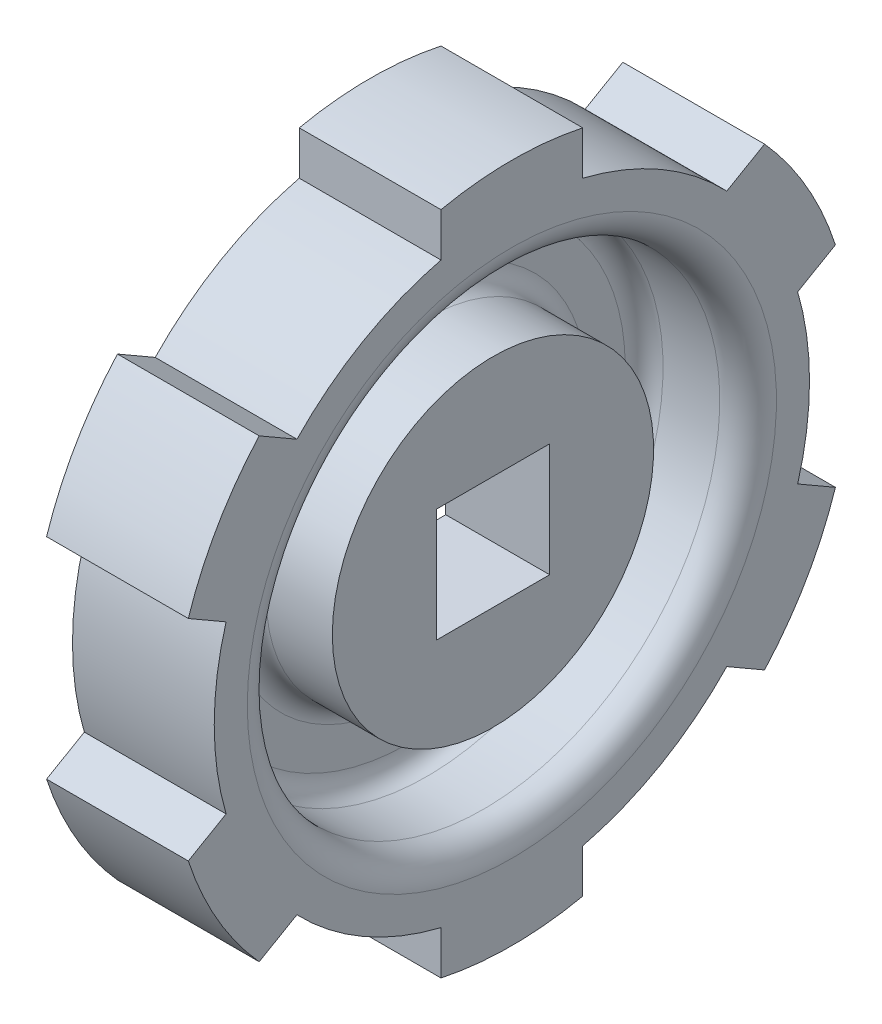
SolidWorks part; units mm, degrees
ref_plane "Спереди" through (0, 0, 0) normal (0, 0, 1) x (1, 0, 0)
ref_plane "Сверху" through (0, 0, 0) normal (0, 1, 0) x (1, 0, 0)
ref_plane "Справа" through (0, 0, 0) normal (1, 0, 0) x (0, 0, -1)
sketch "Эскиз1" plane through (0, 0, 0) normal (0, 0, 1) x (1, 0, 0)
  line L0 (0, 0) -> (126.8227, 0) construction
  line L1 (2, 0) -> (2, 15)
  line L2 (2, 15) -> (0, 15)
  line L3 (0, 15) -> (0, 31.5)
  line L4 (0, 31.5) -> (15, 31.5)
  line L5 (15, 31.5) -> (15, 28)
  line L6 (12, 25) -> (4, 25)
  line L7 (4, 25) -> (4, 17)
  line L8 (4, 17) -> (13, 17)
  line L9 (13, 17) -> (13, 0)
  line L10 (13, 0) -> (2, 0)
  arc A0 (15, 28) -> (12, 25) centre (12, 28) cw
  dimension "D7" = 3
  dimension "D1" = 30
  dimension "D2" = 2
  dimension "D3" = 63
  dimension "D4" = 15
  dimension "D5" = 34
  dimension "D6" = 50
  dimension "D8" = 11
  dimension "D9" = 2
revolve "Повернуть1" add sketch "Эскиз1" angle 360 about L0
sketch "Эскиз2" plane through (2, 0, 0) normal (-1, 0, 0) x (0, 0, 1)
  line L1 (-6, -6) -> (6, -6)
  line L2 (-6, -6) -> (-6, 6)
  line L3 (-6, 6) -> (6, 6)
  line L4 (6, -6) -> (6, 6)
  line L5 (-6, -6) -> (6, 6) construction
  line L6 (-6, 6) -> (6, -6) construction
  point P0 (0, 0)
  dimension "D1" = 12
extrude "Вырез-Вытянуть1" cut sketch "Эскиз2" against normal through all
sketch "Эскиз3" plane through (0, 0, 0) normal (-1, 0, 0) x (0, 0, 1)
  line L0 (0, 31.5) -> (0, 0) construction
  line L2 (-7.5, 41.4059) -> (7.5, 41.4059)
  line L3 (-7.5, 41.4059) -> (-7.5, 30.5941)
  line L4 (-7.5, 30.5941) -> (7.5, 30.5941)
  line L5 (7.5, 41.4059) -> (7.5, 30.5941)
  line L6 (-7.5, 41.4059) -> (7.5, 30.5941) construction
  line L7 (-7.5, 30.5941) -> (7.5, 41.4059) construction
  circle A0 centre (0, 0) radius 31.5 construction
  circle A1 centre (0, 0) radius 36
  point P6 (0, 36)
  circle M2 centre (0, 0) radius 31.5
  dimension "D1" = 72
  dimension "D2" = 15
extrude "Бобышка-Вытянуть1" add sketch "Эскиз3" against normal up to surface (15 mm away) contours L5 A1 L3 M2
pattern_circular "Круговой массив1" count 6 over 360 about axis through (0, 0, 0) along (1, 0, 0) of "Бобышка-Вытянуть1"
fillet "Скругление1" radius 2 2 edges at (4, 0, 17) (4, 0, 25)
